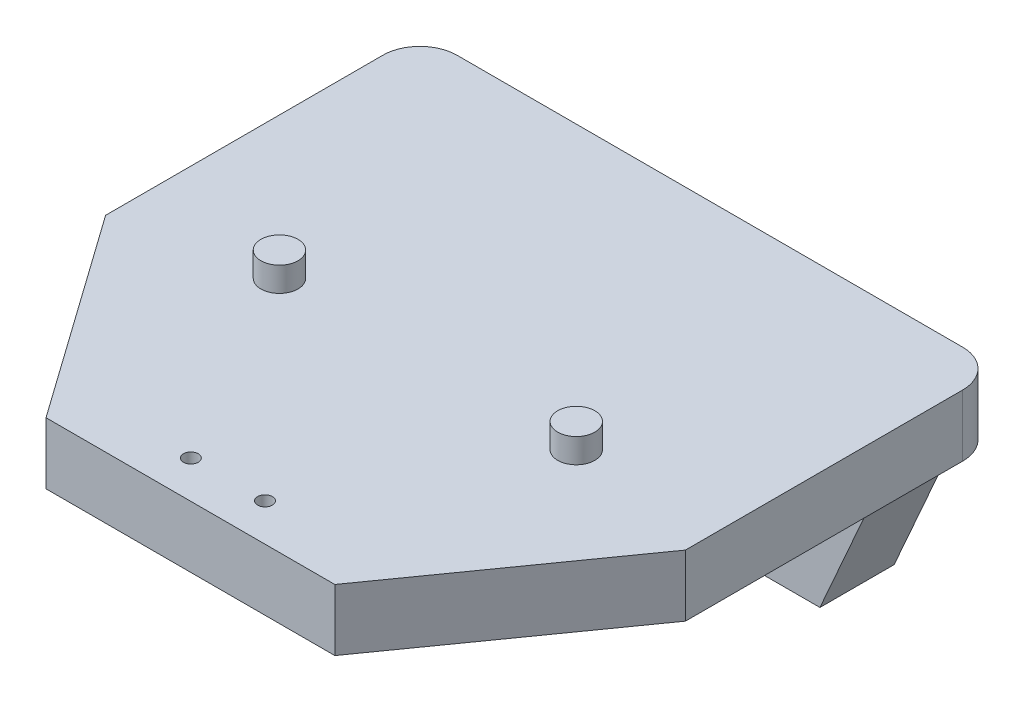
SolidWorks part; units mm, degrees
ref_plane "Front Plane" through (0, 0, 0) normal (0, 0, 1) x (1, 0, 0)
ref_plane "Top Plane" through (0, 0, 0) normal (0, 1, 0) x (1, 0, 0)
ref_plane "Right Plane" through (0, 0, 0) normal (1, 0, 0) x (0, 0, -1)
sketch "Sketch1" plane through (0, 0, 0) normal (0, 0, 1) x (1, 0, 0)
  line L1 (-104.14, 5) -> (-26, 5)
  line L2 (-104.14, 5) -> (-104.14, -3.3031)
  line L3 (-89.9058, -25) -> (-40.2342, -25)
  line L4 (-26, 5) -> (-26, -3.3031)
  line L5 (-104.14, 5) -> (-38.1687, -20.3281) construction
  line L6 (-91.9713, -20.3281) -> (-26, 5) construction
  line L8 (-65.07, -10) -> (-65.07, -38.2553) construction
  line L10 (-104.14, -3.3031) -> (-99.4984, -3.3031)
  line L11 (-99.4984, -3.3031) -> (-89.9058, -25)
  line L12 (-30.6416, -3.3031) -> (-40.2342, -25)
  line L13 (-26, -3.3031) -> (-30.6416, -3.3031)
  point P0 (-65.07, -10)
extrude "Boss-Extrude1" add sketch "Sketch1" along normal blind 10
sketch "Sketch2" plane through (0, 0, 10) normal (0, 0, 1) x (1, 0, 0)
  line L0 (-104.14, 5) -> (-104.14, -3.3031) construction
  line L1 (-26, 5) -> (-104.14, 5)
  line L2 (-26, 5) -> (-26, -3.3)
  line L4 (-104.14, 5) -> (-104.14, -3.3)
  line L5 (-104.14, -3.3) -> (-26, -3.3)
  line L6 (-26, -3.3031) -> (-26, 5) construction
  dimension "D1" = 8.3
extrude "Boss-Extrude2" add sketch "Sketch2" along normal blind 60
sketch "Sketch3" plane through (0, 0, 10) normal (0, 0, 1) x (1, 0, 0)
  line L0 (-65.07, -25) -> (-65.07, 2.0237) construction
  line L1 (-89.9058, -25) -> (-40.2342, -25) construction
  circle A0 centre (-65.07, -13.5) radius 7.5
  dimension "D1" = 15
  dimension "D2" = 11.5
extrude "Cut-Extrude1" cut sketch "Sketch3" against normal blind 10
fillet "Fillet1" radius 5 2 edges at (-26, 0.8485, 0) (-104.14, 0.8485, 0)
sketch "Sketch4" plane through (0, -3.3, 0) normal (0, -1, 0) x (1, 0, 0)
  line L0 (-65.07, 70) -> (-65.07, 0) construction
  line L1 (-104.14, 70) -> (-26, 70) construction
  line L2 (-89.9058, 0) -> (-40.2342, 0) construction
  line L3 (-84.5312, 70) -> (-104.14, 42.3558)
  line L4 (-104.14, 70) -> (-104.14, 10) construction
  line L5 (-45.6088, 70) -> (-26, 42.3558)
  line L6 (-84.5312, 70) -> (-104.14, 70)
  line L7 (-104.14, 70) -> (-104.14, 42.3558)
  line L8 (-45.6088, 70) -> (-26, 70)
  line L9 (-26, 70) -> (-26, 42.3558)
  point P12 (-104.14, 42.3558)
extrude "Cut-Extrude2" cut sketch "Sketch4" against normal blind 10
sketch "Sketch5" plane through (0, -3.3, 0) normal (0, -1, 0) x (1, 0, 0)
  line L0 (-65.07, 70) -> (-65.07, 42.9434) construction
  line L1 (-84.5312, 70) -> (-45.6088, 70) construction
  line L2 (-104.14, 10) -> (-26, 10) construction
  circle A0 centre (-85.07, 38) radius 2.5
  circle A1 centre (-45.07, 38) radius 2.5
  dimension "D2" = 5
  dimension "D3" = 28
  dimension "D1" = 40
extrude "Boss-Extrude3" add sketch "Sketch5" along normal blind 5 contours A0 | A1
mirror "Mirror1" about plane through (0, 0, 0) normal (0, 1, 0) of "Boss-Extrude3"
sketch "Sketch7" plane through (0, -3.3, 0) normal (0, -1, 0) x (1, 0, 0)
  line L0 (-65.07, 70) -> (-65.07, 51.118) construction
  line L1 (-84.5312, 70) -> (-45.6088, 70) construction
  circle A0 centre (-60.07, 64.9453) radius 1
  circle A1 centre (-70.07, 64.9453) radius 1
  dimension "D1" = 2
  dimension "D2" = 10
extrude "Cut-Extrude3" cut sketch "Sketch7" against normal blind 10 contours A0 | A1
ref_plane "Plane1" through (-65.07, 0, 0) normal (-1, 0, 0) x (0, 0, 1)
ref_plane "Plane2" through (0, 0.85, 0) normal (0, 1, 0) x (1, 0, 0)
